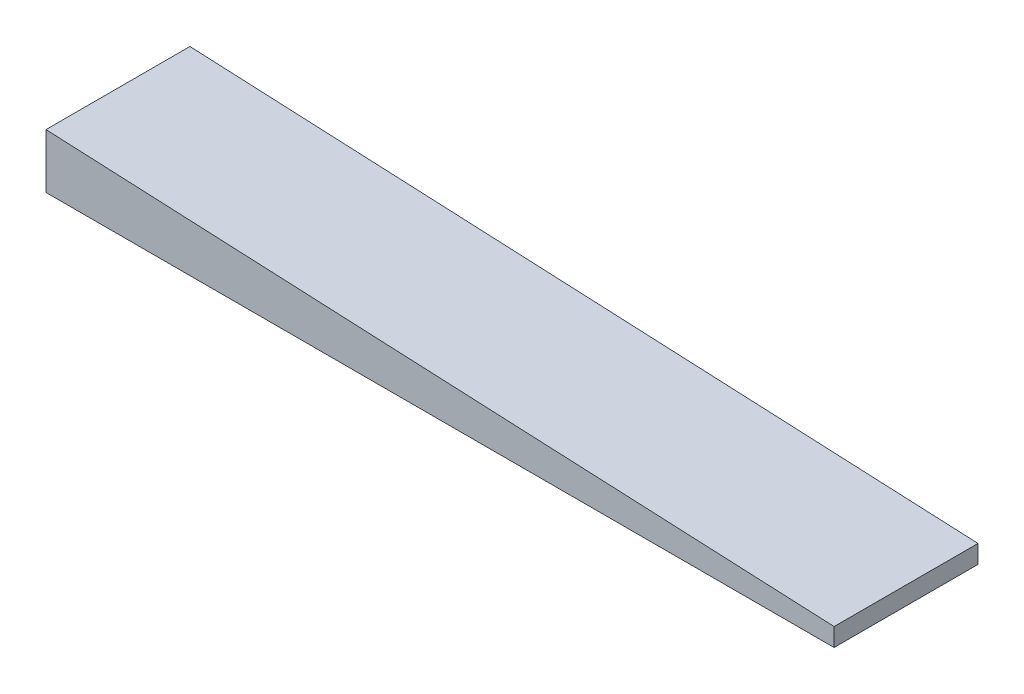
SolidWorks part; units mm, degrees
material "PET"
ref_plane "Front Plane" through (0, 0, 0) normal (0, 0, 1) x (1, 0, 0)
ref_plane "Top Plane" through (0, 0, 0) normal (0, 1, 0) x (1, 0, 0)
ref_plane "Right Plane" through (0, 0, 0) normal (1, 0, 0) x (0, 0, -1)
sketch "Sketch1" plane through (0, 0, 0) normal (0, 0, 1) x (1, 0, 0)
  line L0 (0, 0) -> (0, 24.0505)
  line L1 (0, 24.0505) -> (521.5974, 0)
  line L2 (521.5974, 0) -> (0, 0)
  line L3 (208.639, 0) -> (208.639, 14.4303)
  line L4 (417.278, 0) -> (417.278, 4.8101)
  dimension "D1" = 521.5974
  dimension "D2" = 177.36
  dimension "D3" = 208.639
  dimension "D4" = 104.3195
extrude "Boss-Extrude1" add sketch "Sketch1" along normal blind 38.1 contours L2 L4 L1 L3
